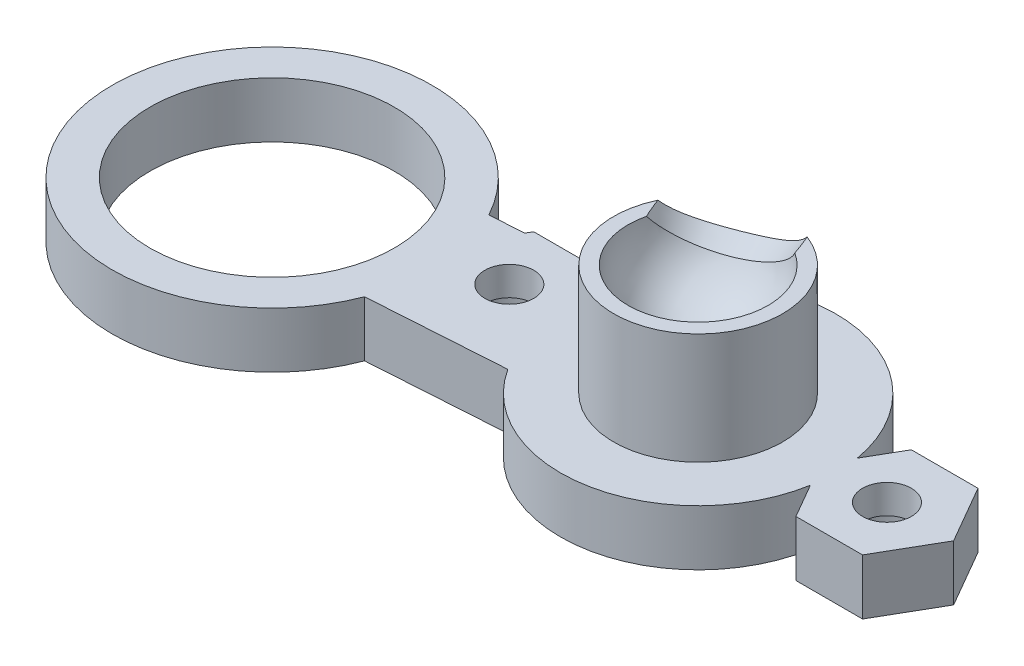
SolidWorks part; units mm, degrees
other "Compression Link 3 Moving Ball Retainer"
ref_plane "Front Plane" through (0, 0, 0) normal (0, 0, 1) x (1, 0, 0)
ref_plane "Top Plane" through (0, 0, 0) normal (0, 1, 0) x (1, 0, 0)
ref_plane "Right Plane" through (0, 0, 0) normal (1, 0, 0) x (0, 0, -1)
sketch3d "Retainer Feature 1 profile datum points"
  point P0 (-56.2917, -101, 30)
  point P1 (-46.2917, -101, 30)
  point P2 (-56.2917, -101, 40)
ref_plane "Retainer Feature 1 profile plane" through (0, -101, 0) normal (0, -1, 0) x (-1, 0, 0)
sketch "Retainer Feature 1 profile" plane through (0, -101, 0) normal (0, -1, 0) x (-1, 0, 0)
  circle A0 centre (56.2917, -30) radius 3.8
extrude "Retainer Feature 1" add sketch "Retainer Feature 1 profile" along normal blind 5.02 separate body
sketch3d "Retainer Feature 2 profile datum points"
  point P0 (-56.2917, -106, 30)
  point P1 (-46.2917, -106, 30)
  point P2 (-56.2917, -106, 40)
ref_plane "Retainer Feature 2 profile plane" through (0, -106, 0) normal (0, -1, 0) x (-1, 0, 0)
sketch "Retainer Feature 2 profile" plane through (0, -106, 0) normal (0, -1, 0) x (-1, 0, 0)
  circle A0 centre (56.2917, -30) radius 6.2
extrude "Retainer Feature 2" add sketch "Retainer Feature 2 profile" along normal blind 2.5
sketch3d "Middle Right Floating Compression Ball Retainer 3 Hexagonal Screw Pad 42 datum points"
  point P0 (-47.7917, -106, 30)
  point P1 (-37.7917, -106, 30)
  point P2 (-47.7917, -106, 40)
ref_plane "Middle Right Floating Compression Ball Retainer 3 Hexagonal Screw Pad 42 plane" through (0, -106, 0) normal (0, -1, 0) x (-1, 0, 0)
sketch "Middle Right Floating Compression Ball Retainer 3 Hexagonal Screw Pad 42" plane through (0, -106, 0) normal (0, -1, 0) x (-1, 0, 0)
  line L0 (44.7917, -30) -> (46.2917, -32.5981)
  line L1 (46.2917, -32.5981) -> (49.2917, -32.5981)
  line L2 (49.2917, -32.5981) -> (50.7917, -30)
  line L3 (50.7917, -30) -> (49.2917, -27.4019)
  line L4 (49.2917, -27.4019) -> (46.2917, -27.4019)
  line L5 (46.2917, -27.4019) -> (44.7917, -30)
extrude "Retainer Feature 5" add sketch "Middle Right Floating Compression Ball Retainer 3 Hexagonal Screw Pad 42" along normal blind 2.5
sketch3d "Middle Right Floating Compression Ball Retainer 3 Hexagonal Screw Pad 45 datum points"
  point P0 (-64.7917, -106, 30)
  point P1 (-54.7917, -106, 30)
  point P2 (-64.7917, -106, 40)
ref_plane "Middle Right Floating Compression Ball Retainer 3 Hexagonal Screw Pad 45 plane" through (0, -106, 0) normal (0, -1, 0) x (-1, 0, 0)
sketch "Middle Right Floating Compression Ball Retainer 3 Hexagonal Screw Pad 45" plane through (0, -106, 0) normal (0, -1, 0) x (-1, 0, 0)
  line L0 (61.7917, -30) -> (63.2917, -32.5981)
  line L1 (63.2917, -32.5981) -> (66.2917, -32.5981)
  line L2 (66.2917, -32.5981) -> (67.7917, -30)
  line L3 (67.7917, -30) -> (66.2917, -27.4019)
  line L4 (66.2917, -27.4019) -> (63.2917, -27.4019)
  line L5 (63.2917, -27.4019) -> (61.7917, -30)
extrude "Retainer Feature 8" add sketch "Middle Right Floating Compression Ball Retainer 3 Hexagonal Screw Pad 45" along normal blind 2.5
sketch3d "Retainer Feature 9 axis line"
  line L0 (-56.2917, -101, 20) -> (-56.2917, -101, 40) construction
ref_axis "Retainer Feature 9 axis" through (-56.2917, -101, 20) along (0, 0, 1)
sketch3d "Retainer Feature 9 profile datum points"
  point P0 (-56.2917, -101, 30)
  point P1 (-46.2917, -101, 30)
  point P2 (-56.2917, -101, 40)
ref_plane "Retainer Feature 9 profile plane" through (0, -101, 0) normal (0, -1, 0) x (-1, 0, 0)
sketch "Retainer Feature 9 profile" plane through (0, -101, 0) normal (0, -1, 0) x (-1, 0, 0)
  line L0 (56.2917, -33.15) -> (56.2917, -26.85)
  arc A0 (56.2917, -26.85) -> (56.2917, -33.15) centre (56.2917, -30) ccw
revolve "Retainer Feature 9" cut sketch "Retainer Feature 9 profile" angle 360 about axis through (-56.2917, -101, 20) along (0, 0, 1)
sketch3d "Middle Right Floating Compression Ball Retainer 3 Plate Sketch 177 datum points"
  point P0 (-56.2917, -106, 30)
  point P1 (-66.2703, -106, 30.6524)
  point P2 (-56.9441, -106, 20.0213)
ref_plane "Middle Right Floating Compression Ball Retainer 3 Plate Sketch 177 plane" through (0, -106, 0) normal (0, -1, 0) x (-1, 0, 0)
sketch "Middle Right Floating Compression Ball Retainer 3 Plate Sketch 177" plane through (0, -106, 0) normal (0, -1, 0) x (-1, 0, 0)
  line L0 (56.0959, -32.9936) -> (74.0959, -34.1705)
  line L1 (74.0959, -34.1705) -> (74.4874, -28.1833)
  line L2 (74.4874, -28.1833) -> (56.4874, -27.0064)
  line L3 (56.4874, -27.0064) -> (56.0959, -32.9936)
extrude "Retainer Feature 12" add sketch "Middle Right Floating Compression Ball Retainer 3 Plate Sketch 177" along normal blind 2.5
sketch3d "Retainer Feature 13 profile datum points"
  point P0 (-74.2917, -106, 31.1769)
  point P1 (-64.2917, -106, 31.1769)
  point P2 (-74.2917, -106, 41.1769)
ref_plane "Retainer Feature 13 profile plane" through (0, -106, 0) normal (0, -1, 0) x (-1, 0, 0)
sketch "Retainer Feature 13 profile" plane through (0, -106, 0) normal (0, -1, 0) x (-1, 0, 0)
  circle A0 centre (74.2917, -31.1769) radius 7.2
extrude "Retainer Feature 13" add sketch "Retainer Feature 13 profile" along normal blind 2.5
sketch3d "Retainer Feature 14 profile datum points"
  point P0 (-74.2917, -105.9, 31.1769)
  point P1 (-64.2917, -105.9, 31.1769)
  point P2 (-74.2917, -105.9, 41.1769)
ref_plane "Retainer Feature 14 profile plane" through (0, -105.9, 0) normal (0, -1, 0) x (-1, 0, 0)
sketch "Retainer Feature 14 profile" plane through (0, -105.9, 0) normal (0, -1, 0) x (-1, 0, 0)
  circle A0 centre (74.2917, -31.1769) radius 5.5
extrude "Retainer Feature 14" cut sketch "Retainer Feature 14 profile" along normal blind 2.7
sketch3d "Retainer Feature 15 profile datum points"
  point P0 (-47.7917, -105, 30)
  point P1 (-37.7917, -105, 30)
  point P2 (-47.7917, -105, 40)
ref_plane "Retainer Feature 15 profile plane" through (0, -105, 0) normal (0, -1, 0) x (-1, 0, 0)
sketch "Retainer Feature 15 profile" plane through (0, -105, 0) normal (0, -1, 0) x (-1, 0, 0)
  circle A0 centre (47.7917, -30) radius 1.1
extrude "Retainer Feature 15" cut sketch "Retainer Feature 15 profile" along normal blind 3.75
sketch3d "Retainer Feature 16 profile datum points"
  point P0 (-47.7917, -107.3, 30)
  point P1 (-37.7917, -107.3, 30)
  point P2 (-47.7917, -107.3, 40)
ref_plane "Retainer Feature 16 profile plane" through (0, -107.3, 0) normal (0, -1, 0) x (-1, 0, 0)
sketch "Retainer Feature 16 profile" plane through (0, -107.3, 0) normal (0, -1, 0) x (-1, 0, 0)
  circle A0 centre (47.7917, -30) radius 2.1
extrude "Retainer Feature 16" cut sketch "Retainer Feature 16 profile" along normal blind 1.45
sketch3d "Retainer Feature 17 profile datum points"
  point P0 (-64.7917, -105, 30)
  point P1 (-54.7917, -105, 30)
  point P2 (-64.7917, -105, 40)
ref_plane "Retainer Feature 17 profile plane" through (0, -105, 0) normal (0, -1, 0) x (-1, 0, 0)
sketch "Retainer Feature 17 profile" plane through (0, -105, 0) normal (0, -1, 0) x (-1, 0, 0)
  circle A0 centre (64.7917, -30) radius 1.1
extrude "Retainer Feature 17" cut sketch "Retainer Feature 17 profile" along normal blind 3.75
sketch3d "Retainer Feature 18 profile datum points"
  point P0 (-64.7917, -107.3, 30)
  point P1 (-54.7917, -107.3, 30)
  point P2 (-64.7917, -107.3, 40)
ref_plane "Retainer Feature 18 profile plane" through (0, -107.3, 0) normal (0, -1, 0) x (-1, 0, 0)
sketch "Retainer Feature 18 profile" plane through (0, -107.3, 0) normal (0, -1, 0) x (-1, 0, 0)
  circle A0 centre (64.7917, -30) radius 2.1
extrude "Retainer Feature 18" cut sketch "Retainer Feature 18 profile" along normal blind 1.45
sketch3d "Articulation Throat axis line"
  line L0 (-53.1481, -106.3831, 37.8192) -> (-59.4352, -95.6169, 22.1808) construction
ref_axis "Articulation Throat axis" through (-53.1481, -106.3831, 37.8192) along (-0.3144, 0.5383, -0.7819)
sketch3d "Articulation Throat Sketch datum points"
  point P0 (-56.2917, -101, 30)
  point P1 (-56.2917, -109.2368, 24.3295)
  point P2 (-59.4352, -95.6169, 22.1808)
ref_plane "Articulation Throat Sketch plane" through (-75.1941, -14.1195, 20.5094) normal (0.9493, 0.1783, -0.2589) x (-0.2545, -0.0478, -0.9659)
sketch "Articulation Throat Sketch" plane through (-75.1941, -14.1195, 20.5094) normal (0.9493, 0.1783, -0.2589) x (-0.2545, -0.0478, -0.9659)
  line L0 (-9.8257, -88.8766) -> (-8.4754, -90.7385)
  line L1 (-8.4754, -90.7385) -> (14.089, -82.6758)
  line L2 (14.089, -82.6758) -> (8.7936, -75.3739)
  line L3 (8.7936, -75.3739) -> (-9.8257, -88.8766)
revolve "Articulation Throat" cut sketch "Articulation Throat Sketch" angle 360 about axis through (-53.1481, -106.3831, 37.8192) along (-0.3144, 0.5383, -0.7819)
